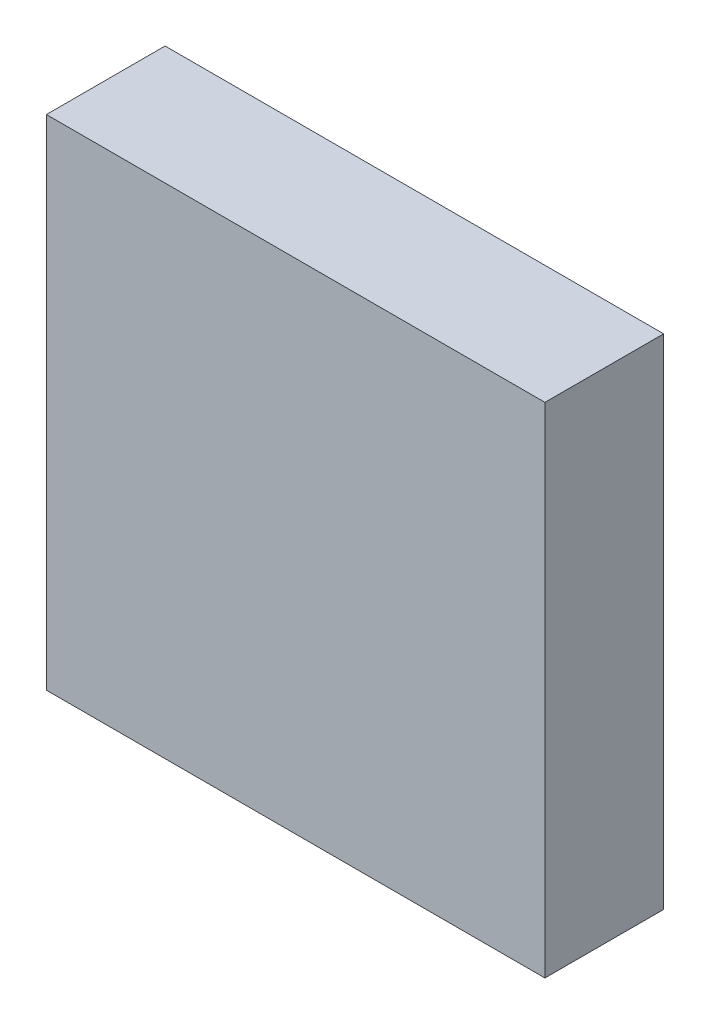
SolidWorks part; units mm, degrees
ref_plane "Front Plane" through (0, 0, 0) normal (0, 0, 1) x (1, 0, 0)
ref_plane "Top Plane" through (0, 0, 0) normal (0, 1, 0) x (1, 0, 0)
ref_plane "Right Plane" through (0, 0, 0) normal (1, 0, 0) x (0, 0, -1)
sketch "Sketch1" plane through (0, 0, 0) normal (0, 0, 1) x (1, 0, 0)
  line L1 (0, 0) -> (21, 0)
  line L2 (0, 0) -> (0, 21)
  line L3 (0, 21) -> (21, 21)
  line L4 (21, 0) -> (21, 21)
  dimension "D1" = 21
extrude "Profile" add sketch "Sketch1" along normal blind 5
equation "\"Profile_Depth\" = 5mm"
equation "\"D1@Profile\" = \"Profile_Depth\""
equation "\"Profile_Sketch_1\" = 21mm"
equation "\"D1@Sketch1\" = \"Profile_Sketch_1\""
equation "\"EnvelopeWidth\" = 21mm"
equation "\"EnvelopeHeight\" = 21mm"
